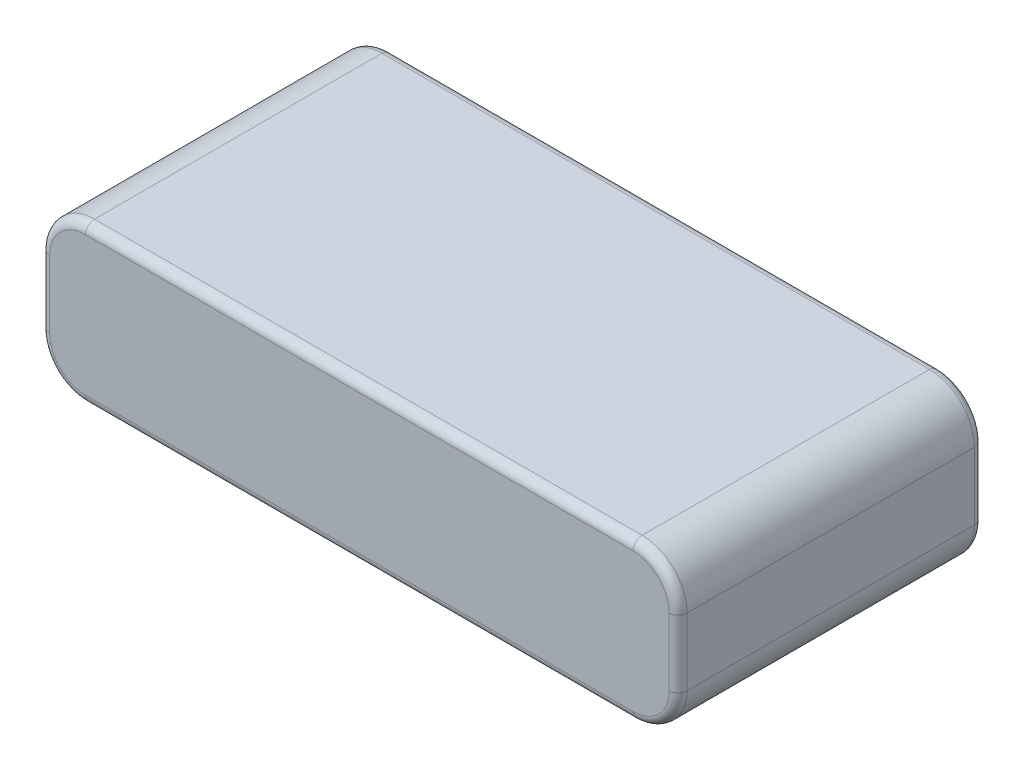
SolidWorks part; units mm, degrees
ref_plane "Front Plane" through (0, 0, 0) normal (0, 0, 1) x (1, 0, 0)
ref_plane "Top Plane" through (0, 0, 0) normal (0, 1, 0) x (1, 0, 0)
ref_plane "Right Plane" through (0, 0, 0) normal (1, 0, 0) x (0, 0, -1)
sketch "Sketch2" plane through (0, 0, 0) normal (0, 1, 0) x (1, 0, 0)
  line L1 (-35.5, 17) -> (35.5, 17)
  line L2 (-35.5, 17) -> (-35.5, -17)
  line L3 (-35.5, -17) -> (35.5, -17)
  line L4 (35.5, 17) -> (35.5, -17)
  line L5 (-35.5, 17) -> (35.5, -17) construction
  line L6 (-35.5, -17) -> (35.5, 17) construction
  point P0 (0, 0)
  dimension "D1" = 71
  dimension "D2" = 34
extrude "Boss-Extrude1" add sketch "Sketch2" along normal blind 17.5
fillet "Fillet1" radius 5 4 edges at (-35.5, 0, 0) (35.5, 0, 0) (35.5, 17.5, 0) (-35.5, 17.5, 0)
fillet "Fillet2" radius 1 16 edges at (34.0355, 1.4645, -17) (35.5, 8.75, -17) (34.0355, 16.0355, -17) (0, 17.5, -17) (-34.0355, 16.0355, -17) (-35.5, 8.75, -17) (-34.0355, 1.4645, -17) (0, 0, -17) (-34.0355, 16.0355, 17) (0, 17.5, 17) (34.0355, 16.0355, 17) (35.5, 8.75, 17) (34.0355, 1.4645, 17) (0, 0, 17) (-34.0355, 1.4645, 17) (-35.5, 8.75, 17)
